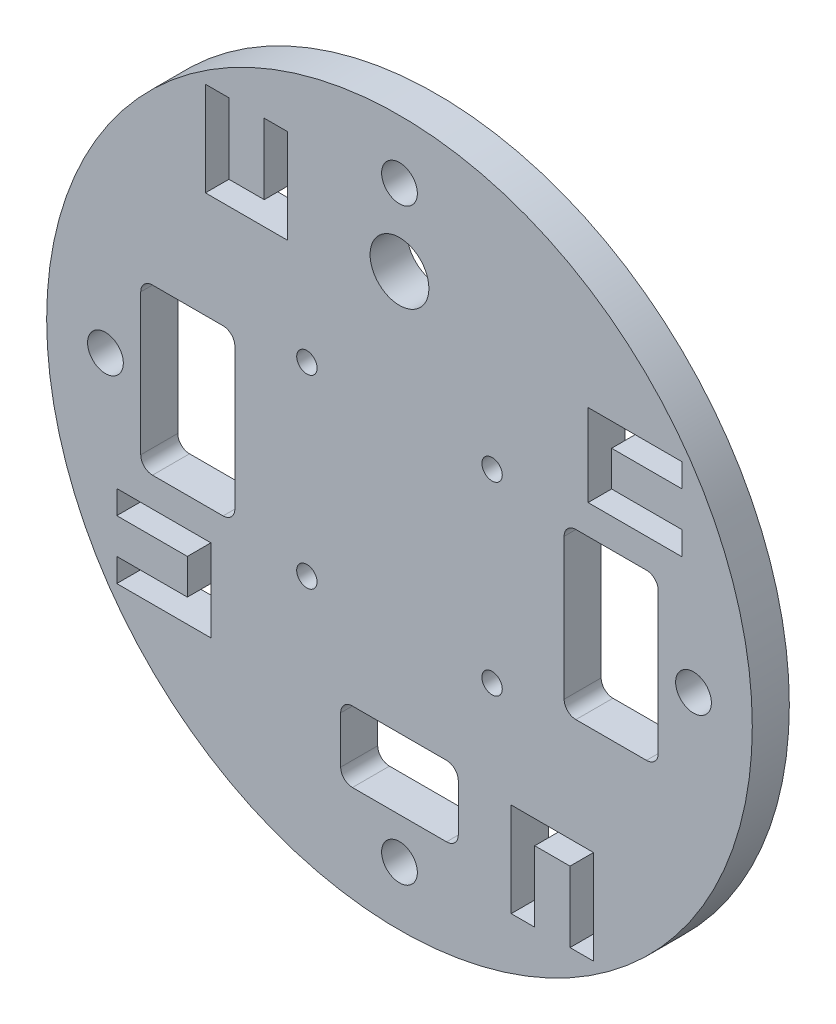
SolidWorks part; units mm, degrees
material "Hexcel AS4C (3000 Filaments)"
ref_plane "Front Plane" through (0, 0, 0) normal (0, 0, 1) x (1, 0, 0)
ref_plane "Top Plane" through (0, 0, 0) normal (0, 1, 0) x (1, 0, 0)
ref_plane "Right Plane" through (0, 0, 0) normal (1, 0, 0) x (0, 0, -1)
sketch "Sketch1" plane through (0, 0, 0) normal (0, 0, 1) x (1, 0, 0)
  circle A0 centre (0, 0) radius 38.1
  dimension "D1" = 76.2
extrude "Boss-Extrude1" add sketch "Sketch1" along normal blind 4 contours A0
sketch "Sketch2" plane through (0, 0, 4) normal (0, 0, 1) x (1, 0, 0)
  circle A0 centre (10, 10) radius 1.1
  circle A1 centre (10, -10) radius 1.1
  circle A2 centre (-10, -10) radius 1.1
  circle A3 centre (-10, 10) radius 1.1
  point P12 (0, 0)
  point P21 (0, 0)
  dimension "D3" = 2.2
  dimension "D1" = 10
  dimension "D2" = 10
  dimension "D4" = 4
extrude "Cut-Extrude1" cut sketch "Sketch2" against normal through all
sketch "Sketch3" plane through (0, 0, 4) normal (0, 0, 1) x (1, 0, 0)
  circle A0 centre (0, -31.75) radius 1.9304
  circle A1 centre (-31.75, 0) radius 1.9304
  circle A2 centre (0, 31.75) radius 1.9304
  circle A3 centre (31.75, 0) radius 1.9304
  point P9 (0, 0)
  dimension "D2" = 3.8608
  dimension "D1" = 31.75
  dimension "D3" = 4
extrude "Cut-Extrude2" cut sketch "Sketch3" against normal through all both and the other way through all
sketch "Sketch4" plane through (0, 0, 4) normal (0, 0, 1) x (1, 0, 0)
  line L0 (-19.05, -8.89) -> (-26.67, -8.89)
  line L1 (19.05, 8.89) -> (26.67, 8.89)
  line L2 (17.78, 7.62) -> (17.78, -7.62)
  line L3 (19.05, -8.89) -> (26.67, -8.89)
  line L4 (27.94, 7.62) -> (27.94, -7.62)
  line L5 (-17.78, -7.62) -> (-17.78, 7.62)
  line L6 (-19.05, 8.89) -> (-26.67, 8.89)
  line L7 (-27.94, -7.62) -> (-27.94, 7.62)
  arc A0 (17.78, -7.62) -> (19.05, -8.89) centre (19.05, -7.62) ccw
  arc A1 (26.67, -8.89) -> (27.94, -7.62) centre (26.67, -7.62) ccw
  arc A2 (26.67, 8.89) -> (27.94, 7.62) centre (26.67, 7.62) cw
  arc A3 (19.05, 8.89) -> (17.78, 7.62) centre (19.05, 7.62) ccw
  arc A4 (-17.78, 7.62) -> (-19.05, 8.89) centre (-19.05, 7.62) ccw
  arc A5 (-26.67, 8.89) -> (-27.94, 7.62) centre (-26.67, 7.62) ccw
  arc A6 (-26.67, -8.89) -> (-27.94, -7.62) centre (-26.67, -7.62) cw
  arc A7 (-19.05, -8.89) -> (-17.78, -7.62) centre (-19.05, -7.62) ccw
  point P4 (17.78, 0)
  point P8 (17.78, -8.89)
  point P15 (17.78, 8.89)
  point P16 (0, 0)
  point P17 (0, 0)
  point P30 (0, 0)
  point P31 (-17.7969, 9.5588)
  point P32 (-17.78, 0)
  dimension "D4" = 1.27
  dimension "D1" = 10.16
  dimension "D2" = 17.78
  dimension "D3" = 17.78
  dimension "D5" = 2
extrude "Cut-Extrude3" cut sketch "Sketch4" against normal through all both and the other way through all
sketch "Sketch5" plane through (0, 0, 4) normal (0, 0, 1) x (1, 0, 0)
  line L0 (0, 23.495) -> (0, -23.495) construction
  line L2 (-5.08, -27.305) -> (5.08, -27.305)
  line L3 (-6.35, -26.035) -> (-6.35, -20.955)
  line L4 (-5.08, -19.685) -> (5.08, -19.685)
  line L5 (6.35, -26.035) -> (6.35, -20.955)
  line L6 (-6.35, -27.305) -> (6.35, -19.685) construction
  line L7 (-6.35, -19.685) -> (6.35, -27.305) construction
  circle A0 centre (0, 23.495) radius 3.175
  arc A1 (-6.35, -20.955) -> (-5.08, -19.685) centre (-5.08, -20.955) cw
  arc A2 (-5.08, -27.305) -> (-6.35, -26.035) centre (-5.08, -26.035) cw
  arc A3 (5.08, -27.305) -> (6.35, -26.035) centre (5.08, -26.035) ccw
  arc A4 (5.08, -19.685) -> (6.35, -20.955) centre (5.08, -20.955) cw
  point P4 (0, 0)
  dimension "D2" = 6.35
  dimension "D5" = 1.27
  dimension "D1" = 46.99
  dimension "D3" = 12.7
  dimension "D4" = 7.62
extrude "Cut-Extrude4" cut sketch "Sketch5" against normal up to next
sketch "Sketch6" plane through (0, 0, 4) normal (0, 0, 1) x (1, 0, 0)
  line L1 (-19.05, 38.147) -> (-13.97, 38.147) construction
  line L2 (-19.05, 38.147) -> (-19.05, 30.527) construction
  line L3 (-19.05, 30.527) -> (-13.97, 30.527) construction
  line L4 (-13.97, 38.147) -> (-13.97, 30.527) construction
  line L5 (-19.05, 38.147) -> (-13.97, 30.527) construction
  line L6 (-19.05, 30.527) -> (-13.97, 38.147) construction
  line L8 (-18.415, 22.907) -> (-14.605, 22.907)
  line L11 (-12.065, 30.527) -> (-12.065, 20.367)
  line L12 (-12.065, 20.367) -> (-20.955, 20.367)
  line L13 (-20.955, 20.367) -> (-20.955, 30.527)
  line L14 (-18.415, 22.907) -> (-18.415, 30.527)
  line L15 (-18.415, 30.527) -> (-20.955, 30.527)
  line L16 (-14.605, 22.907) -> (-14.605, 30.527)
  line L17 (-14.605, 30.527) -> (-12.065, 30.527)
  line L18 (22.907, 18.415) -> (22.907, 14.605)
  line L19 (30.527, 12.065) -> (20.367, 12.065)
  line L20 (20.367, 12.065) -> (20.367, 20.955)
  line L21 (20.367, 20.955) -> (30.527, 20.955)
  line L22 (22.907, 18.415) -> (30.527, 18.415)
  line L23 (30.527, 18.415) -> (30.527, 20.955)
  line L24 (22.907, 14.605) -> (30.527, 14.605)
  line L25 (30.527, 14.605) -> (30.527, 12.065)
  line L26 (38.147, 19.05) -> (38.147, 13.97) construction
  line L27 (38.147, 19.05) -> (30.527, 19.05) construction
  line L28 (30.527, 19.05) -> (30.527, 13.97) construction
  line L29 (38.147, 13.97) -> (30.527, 13.97) construction
  line L30 (38.147, 19.05) -> (30.527, 13.97) construction
  line L31 (30.527, 19.05) -> (38.147, 13.97) construction
  line L32 (18.415, -22.907) -> (14.605, -22.907)
  line L33 (12.065, -30.527) -> (12.065, -20.367)
  line L34 (12.065, -20.367) -> (20.955, -20.367)
  line L35 (20.955, -20.367) -> (20.955, -30.527)
  line L36 (18.415, -22.907) -> (18.415, -30.527)
  line L37 (18.415, -30.527) -> (20.955, -30.527)
  line L38 (14.605, -22.907) -> (14.605, -30.527)
  line L39 (14.605, -30.527) -> (12.065, -30.527)
  line L40 (19.05, -38.147) -> (13.97, -38.147) construction
  line L41 (19.05, -38.147) -> (19.05, -30.527) construction
  line L42 (19.05, -30.527) -> (13.97, -30.527) construction
  line L43 (13.97, -38.147) -> (13.97, -30.527) construction
  line L44 (19.05, -38.147) -> (13.97, -30.527) construction
  line L45 (19.05, -30.527) -> (13.97, -38.147) construction
  line L46 (-22.907, -18.415) -> (-22.907, -14.605)
  line L47 (-30.527, -12.065) -> (-20.367, -12.065)
  line L48 (-20.367, -12.065) -> (-20.367, -20.955)
  line L49 (-20.367, -20.955) -> (-30.527, -20.955)
  line L50 (-22.907, -18.415) -> (-30.527, -18.415)
  line L51 (-30.527, -18.415) -> (-30.527, -20.955)
  line L52 (-22.907, -14.605) -> (-30.527, -14.605)
  line L53 (-30.527, -14.605) -> (-30.527, -12.065)
  line L54 (-38.147, -19.05) -> (-38.147, -13.97) construction
  line L55 (-38.147, -19.05) -> (-30.527, -19.05) construction
  line L56 (-30.527, -19.05) -> (-30.527, -13.97) construction
  line L57 (-38.147, -13.97) -> (-30.527, -13.97) construction
  line L58 (-38.147, -19.05) -> (-30.527, -13.97) construction
  line L59 (-30.527, -19.05) -> (-38.147, -13.97) construction
  circle A1 centre (0, 0) radius 38.1 construction
  circle A2 centre (0, 31.75) radius 1.9304 construction
  point P0 (-16.51, 34.337)
  point P5 (-15.0519, 35.0007)
  point P14 (-16.51, 22.907)
  point P21 (34.337, 16.51)
  point P34 (16.51, -34.337)
  point P47 (-34.337, -16.51)
  point P60 (0, 0)
  dimension "D1" = 13.97
  dimension "D2" = 5.08
  dimension "D3" = 3.81
  dimension "D4" = 2.54
  dimension "D5" = 2.54
  dimension "D6" = 7.62
  dimension "D7" = 2.54
  dimension "D8" = 7.62
  dimension "D9" = 4
extrude "Cut-Extrude5" cut sketch "Sketch6" against normal up to next
